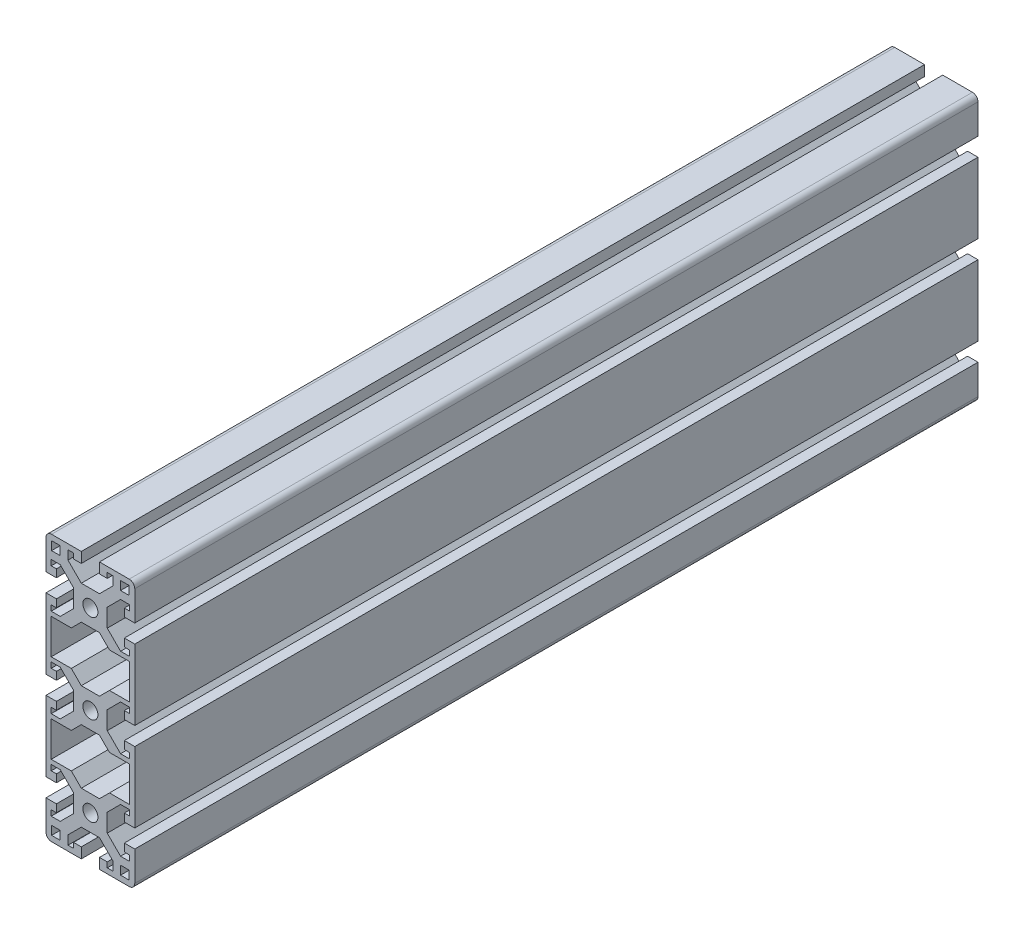
SolidWorks part; units mm, degrees
material "6063-T6"
ref_plane "Front Plane" through (0, 0, 0) normal (0, 0, 1) x (1, 0, 0)
ref_plane "Top Plane" through (0, 0, 0) normal (0, 1, 0) x (1, 0, 0)
ref_plane "Right Plane" through (0, 0, 0) normal (1, 0, 0) x (0, 0, -1)
sketch "Sketch1" plane through (0, 0, 0) normal (0, 1, 0) x (1, 0, 0)
  line L0 (0, 190) -> (0, -190)
  dimension "D1" = 380
other "40 series TS40-120LM(1)"
ref_plane "Plane1" through (0, 0, -190) normal (0, 0, 1) x (1, 0, 0)
sketch "Sketch2" plane through (0, 0, -190) normal (0, 0, 1) x (1, 0, 0)
  line L0 (15.3, -35.9) -> (20, -35.9)
  line L1 (3.35, 0) -> (7.6, 0) construction
  line L2 (7.6, 4.1) -> (7.6, -4.1)
  line L3 (7.6, -4.1) -> (13.6, -10.1)
  line L4 (13.6, -10.1) -> (17.65, -10.1)
  line L5 (17.65, -10.1) -> (17.65, -7.6)
  line L6 (17.65, -7.6) -> (15.3, -7.6)
  line L7 (15.3, -7.6) -> (15.3, -4.1)
  line L8 (15.3, -4.1) -> (20, -4.1)
  line L9 (20, -4.1) -> (20, -35.9)
  line L10 (0, -3.35) -> (0, -7.6) construction
  line L11 (-4.1, -7.6) -> (4.1, -7.6)
  line L12 (4.1, -7.6) -> (8.6, -12.1)
  line L13 (8.6, -12.1) -> (17.65, -12.1)
  line L14 (17.65, -12.1) -> (17.65, -27.9)
  line L15 (20, -20) -> (0, 0) construction
  line L16 (17.65, -20) -> (20, -20) construction
  line L17 (15.3, -32.4) -> (15.3, -35.9)
  line L18 (17.65, -32.4) -> (15.3, -32.4)
  line L19 (17.65, -29.9) -> (17.65, -32.4)
  line L20 (13.6, -29.9) -> (17.65, -29.9)
  line L21 (8.6, -27.9) -> (17.65, -27.9)
  line L22 (7.6, -35.9) -> (13.6, -29.9)
  line L23 (7.6, -44.1) -> (7.6, -35.9)
  line L24 (4.1, -32.4) -> (8.6, -27.9)
  line L25 (-4.1, -32.4) -> (4.1, -32.4)
  line L26 (3.35, -40) -> (7.6, -40) construction
  line L27 (15.3, -44.1) -> (20, -44.1)
  line L28 (15.3, -47.6) -> (15.3, -44.1)
  line L29 (17.65, -47.6) -> (15.3, -47.6)
  line L30 (17.65, -50.1) -> (17.65, -47.6)
  line L31 (13.6, -50.1) -> (17.65, -50.1)
  line L32 (7.6, -44.1) -> (13.6, -50.1)
  line L33 (0, -40) -> (19.2678, -59.2678) construction
  line L34 (20, -57.5) -> (20, -44.1)
  line L35 (17.5, -60) -> (4.1, -60)
  line L36 (4.1, -55.3) -> (4.1, -60)
  line L37 (7.6, -55.3) -> (4.1, -55.3)
  line L38 (7.6, -57.65) -> (7.6, -55.3)
  line L39 (10.1, -57.65) -> (7.6, -57.65)
  line L40 (10.1, -53.6) -> (10.1, -57.65)
  line L41 (4.1, -47.6) -> (10.1, -53.6)
  line L42 (4.1, -47.6) -> (-4.1, -47.6)
  line L43 (0, -40) -> (-19.2678, -59.2678) construction
  line L44 (-3.35, -40) -> (-7.6, -40) construction
  line L45 (-17.65, -20) -> (-20, -20) construction
  line L46 (-20, -20) -> (0, 0) construction
  line L47 (-3.35, 0) -> (-7.6, 0) construction
  line L48 (-4.1, -47.6) -> (-10.1, -53.6)
  line L49 (-10.1, -53.6) -> (-10.1, -57.65)
  line L50 (-10.1, -57.65) -> (-7.6, -57.65)
  line L51 (-7.6, -57.65) -> (-7.6, -55.3)
  line L52 (-7.6, -55.3) -> (-4.1, -55.3)
  line L53 (-4.1, -55.3) -> (-4.1, -60)
  line L54 (-17.5, -60) -> (-4.1, -60)
  line L55 (-20, -57.5) -> (-20, -44.1)
  line L56 (-7.6, -44.1) -> (-13.6, -50.1)
  line L57 (-13.6, -50.1) -> (-17.65, -50.1)
  line L58 (-17.65, -50.1) -> (-17.65, -47.6)
  line L59 (-17.65, -47.6) -> (-15.3, -47.6)
  line L60 (-15.3, -47.6) -> (-15.3, -44.1)
  line L61 (-15.3, -44.1) -> (-20, -44.1)
  line L62 (-4.1, -32.4) -> (-8.6, -27.9)
  line L63 (-7.6, -44.1) -> (-7.6, -35.9)
  line L64 (-7.6, -35.9) -> (-13.6, -29.9)
  line L65 (-8.6, -27.9) -> (-17.65, -27.9)
  line L66 (-13.6, -29.9) -> (-17.65, -29.9)
  line L67 (-17.65, -29.9) -> (-17.65, -32.4)
  line L68 (-17.65, -32.4) -> (-15.3, -32.4)
  line L69 (-15.3, -32.4) -> (-15.3, -35.9)
  line L70 (-17.65, -12.1) -> (-17.65, -27.9)
  line L71 (-8.6, -12.1) -> (-17.65, -12.1)
  line L72 (-4.1, -7.6) -> (-8.6, -12.1)
  line L73 (-20, -4.1) -> (-20, -35.9)
  line L74 (-15.3, -4.1) -> (-20, -4.1)
  line L75 (-15.3, -7.6) -> (-15.3, -4.1)
  line L76 (-17.65, -7.6) -> (-15.3, -7.6)
  line L77 (-17.65, -10.1) -> (-17.65, -7.6)
  line L78 (-13.6, -10.1) -> (-17.65, -10.1)
  line L79 (-7.6, -4.1) -> (-13.6, -10.1)
  line L80 (-7.6, 4.1) -> (-7.6, -4.1)
  line L81 (-15.3, -35.9) -> (-20, -35.9)
  line L82 (-20, 20) -> (0, 0) construction
  line L83 (-17.65, 20) -> (-20, 20) construction
  line L84 (-3.35, 40) -> (-7.6, 40) construction
  line L85 (0, 40) -> (-19.2678, 59.2678) construction
  line L86 (0, 40) -> (19.2678, 59.2678) construction
  line L87 (3.35, 40) -> (7.6, 40) construction
  line L88 (17.65, 20) -> (20, 20) construction
  line L89 (20, 20) -> (0, 0) construction
  line L90 (0, 3.35) -> (0, 7.6) construction
  line L91 (-15.3, 35.9) -> (-20, 35.9)
  line L92 (-7.6, 4.1) -> (-13.6, 10.1)
  line L93 (-13.6, 10.1) -> (-17.65, 10.1)
  line L94 (-17.65, 10.1) -> (-17.65, 7.6)
  line L95 (-17.65, 7.6) -> (-15.3, 7.6)
  line L96 (-15.3, 7.6) -> (-15.3, 4.1)
  line L97 (-15.3, 4.1) -> (-20, 4.1)
  line L98 (-20, 4.1) -> (-20, 35.9)
  line L99 (-4.1, 7.6) -> (-8.6, 12.1)
  line L100 (-8.6, 12.1) -> (-17.65, 12.1)
  line L101 (-17.65, 12.1) -> (-17.65, 27.9)
  line L102 (-15.3, 32.4) -> (-15.3, 35.9)
  line L103 (-17.65, 32.4) -> (-15.3, 32.4)
  line L104 (-17.65, 29.9) -> (-17.65, 32.4)
  line L105 (-13.6, 29.9) -> (-17.65, 29.9)
  line L106 (-8.6, 27.9) -> (-17.65, 27.9)
  line L107 (-7.6, 35.9) -> (-13.6, 29.9)
  line L108 (-7.6, 44.1) -> (-7.6, 35.9)
  line L109 (-4.1, 32.4) -> (-8.6, 27.9)
  line L110 (-15.3, 44.1) -> (-20, 44.1)
  line L111 (-15.3, 47.6) -> (-15.3, 44.1)
  line L112 (-17.65, 47.6) -> (-15.3, 47.6)
  line L113 (-17.65, 50.1) -> (-17.65, 47.6)
  line L114 (-13.6, 50.1) -> (-17.65, 50.1)
  line L115 (-7.6, 44.1) -> (-13.6, 50.1)
  line L116 (-20, 57.5) -> (-20, 44.1)
  line L117 (-17.5, 60) -> (-4.1, 60)
  line L118 (-4.1, 55.3) -> (-4.1, 60)
  line L119 (-7.6, 55.3) -> (-4.1, 55.3)
  line L120 (-7.6, 57.65) -> (-7.6, 55.3)
  line L121 (-10.1, 57.65) -> (-7.6, 57.65)
  line L122 (-10.1, 53.6) -> (-10.1, 57.65)
  line L123 (-4.1, 47.6) -> (-10.1, 53.6)
  line L124 (4.1, 47.6) -> (-4.1, 47.6)
  line L125 (4.1, 47.6) -> (10.1, 53.6)
  line L126 (10.1, 53.6) -> (10.1, 57.65)
  line L127 (10.1, 57.65) -> (7.6, 57.65)
  line L128 (7.6, 57.65) -> (7.6, 55.3)
  line L129 (7.6, 55.3) -> (4.1, 55.3)
  line L130 (4.1, 55.3) -> (4.1, 60)
  line L131 (17.5, 60) -> (4.1, 60)
  line L132 (20, 57.5) -> (20, 44.1)
  line L133 (7.6, 44.1) -> (13.6, 50.1)
  line L134 (13.6, 50.1) -> (17.65, 50.1)
  line L135 (17.65, 50.1) -> (17.65, 47.6)
  line L136 (17.65, 47.6) -> (15.3, 47.6)
  line L137 (15.3, 47.6) -> (15.3, 44.1)
  line L138 (15.3, 44.1) -> (20, 44.1)
  line L139 (-4.1, 32.4) -> (4.1, 32.4)
  line L140 (4.1, 32.4) -> (8.6, 27.9)
  line L141 (7.6, 44.1) -> (7.6, 35.9)
  line L142 (7.6, 35.9) -> (13.6, 29.9)
  line L143 (8.6, 27.9) -> (17.65, 27.9)
  line L144 (13.6, 29.9) -> (17.65, 29.9)
  line L145 (17.65, 29.9) -> (17.65, 32.4)
  line L146 (17.65, 32.4) -> (15.3, 32.4)
  line L147 (15.3, 32.4) -> (15.3, 35.9)
  line L148 (17.65, 12.1) -> (17.65, 27.9)
  line L149 (8.6, 12.1) -> (17.65, 12.1)
  line L150 (4.1, 7.6) -> (8.6, 12.1)
  line L151 (-4.1, 7.6) -> (4.1, 7.6)
  line L152 (20, 4.1) -> (20, 35.9)
  line L153 (15.3, 4.1) -> (20, 4.1)
  line L154 (15.3, 7.6) -> (15.3, 4.1)
  line L155 (17.65, 7.6) -> (15.3, 7.6)
  line L156 (17.65, 10.1) -> (17.65, 7.6)
  line L157 (13.6, 10.1) -> (17.65, 10.1)
  line L158 (7.6, 4.1) -> (13.6, 10.1)
  line L159 (15.3, 35.9) -> (20, 35.9)
  line L161 (13.6, -53.6) -> (17.5, -53.6)
  line L162 (13.6, -53.6) -> (13.6, -57.5)
  line L163 (13.6, -57.5) -> (17.5, -57.5)
  line L164 (17.5, -53.6) -> (17.5, -57.5)
  line L165 (-17.5, -57.5) -> (-13.6, -57.5)
  line L166 (-17.5, -57.5) -> (-17.5, -53.6)
  line L167 (-17.5, -53.6) -> (-13.6, -53.6)
  line L168 (-13.6, -57.5) -> (-13.6, -53.6)
  line L169 (-17.5, 57.5) -> (-13.6, 57.5)
  line L170 (-17.5, 57.5) -> (-17.5, 53.6)
  line L171 (-17.5, 53.6) -> (-13.6, 53.6)
  line L172 (-13.6, 57.5) -> (-13.6, 53.6)
  line L173 (17.5, 57.5) -> (13.6, 57.5)
  line L174 (17.5, 57.5) -> (17.5, 53.6)
  line L175 (17.5, 53.6) -> (13.6, 53.6)
  line L176 (13.6, 57.5) -> (13.6, 53.6)
  arc A0 (0, -43.35) -> (0, -36.65) centre (0, -40) ccw
  arc A1 (3.35, 0) -> (-3.35, 0) centre (0, 0) cw
  arc A2 (17.5, -60) -> (20, -57.5) centre (17.5, -57.5) ccw
  arc A3 (-17.5, -60) -> (-20, -57.5) centre (-17.5, -57.5) cw
  arc A4 (0, -43.35) -> (0, -36.65) centre (0, -40) cw
  arc A5 (0, 43.35) -> (0, 36.65) centre (0, 40) ccw
  arc A6 (-17.5, 60) -> (-20, 57.5) centre (-17.5, 57.5) ccw
  arc A7 (17.5, 60) -> (20, 57.5) centre (17.5, 57.5) cw
  arc A8 (3.35, 0) -> (-3.35, 0) centre (0, 0) ccw
  arc A9 (0, 43.35) -> (0, 36.65) centre (0, 40) cw
  point P19 (17.65, -4.1)
  point P65 (0, -47.6)
  point P79 (0, -32.4)
  point P196 (0, 32.4)
  point P197 (0, 47.6)
  point P201 (20, -60)
  point P202 (-20, -60)
  point P203 (20, -40)
  point P204 (-20, -40)
  point P205 (20, -20)
  point P206 (0, -60)
  point P207 (0, -40)
  point P208 (-20, -20)
  point P209 (-20, 0)
  point P210 (20, 0)
  point P211 (20, 40)
  point P212 (0, 0)
  point P213 (-20, 20)
  point P214 (20, 20)
  point P215 (-20, 40)
  point P216 (0, 40)
  point P217 (20, 60)
  point P218 (0, 60)
  point P219 (-20, 60)
  point P220 (0, 20)
  point P221 (0, -20)
  point P222 (0, 0)
  dimension "D2" = 4.1
  dimension "D4" = 12.4
  dimension "D9" = 2.5
  dimension "D3" = 3.35
  dimension "D5" = 20
  dimension "D10" = 20
  dimension "D6" = 10.1
  dimension "D8" = 2
  dimension "D11" = 2.5
  dimension "D7" = 4.7
hole_wizard "M8x1.25 Tapped Hole1" positions "Sketch3" profile "Sketch4" tap size "M8x1.25" standard "ANSI Metric"
sketch "Sketch3" plane through (0, 0, 190) normal (0, 0, 1) x (1, 0, 0)
  point P0 (0, 40)
  point P3 (0, 0)
  point P6 (0, -40)
sketch "Sketch4" plane through (0, 40, 190) normal (1, 0, 0) x (0, -1, 0)
  line L0 (0, 0) -> (0, 32.0429)
  line L1 (0, 32.0429) -> (3.4, 30)
  line L2 (3.4, 30) -> (3.4, 0)
  line L5 (3.4, 0) -> (0, 0)
  line L10 (0, 32.0429) -> (-3.4, 30) construction
  line L11 (0, -6.35) -> (0, 107.95) construction
  dimension "Tap Drill Dia." = 6.8
  dimension "Tap Drill Depth" = 30
  dimension "Drill Angle" = 118
cosmetic thread "Hole Thread1" parameters "D1"=25, "D2"=8
cosmetic thread "Hole Thread2" parameters "D1"=25, "D2"=8
cosmetic thread "Hole Thread3" parameters "D1"=25, "D2"=8
hole_wizard "M8x1.25 Tapped Hole2" positions "Sketch5" profile "Sketch6" tap size "M8x1.25" standard "ANSI Metric"
sketch "Sketch5" plane through (0, 0, -190) normal (0, 0, -1) x (-1, 0, 0)
  point P0 (0, 40)
  point P3 (0, 0)
sketch "Sketch6" plane through (0, 40, -190) normal (1, 0, 0) x (0, 1, 0)
  line L0 (0, 0) -> (0, 32.0429)
  line L1 (0, 32.0429) -> (3.4, 30)
  line L2 (3.4, 30) -> (3.4, 0)
  line L5 (3.4, 0) -> (0, 0)
  line L10 (0, 32.0429) -> (-3.4, 30) construction
  line L11 (0, -6.35) -> (0, 107.95) construction
  dimension "Tap Drill Dia." = 6.8
  dimension "Tap Drill Depth" = 30
  dimension "Drill Angle" = 118
cosmetic thread "Hole Thread4" parameters "D1"=25, "D2"=8
cosmetic thread "Hole Thread5" parameters "D1"=25, "D2"=8
